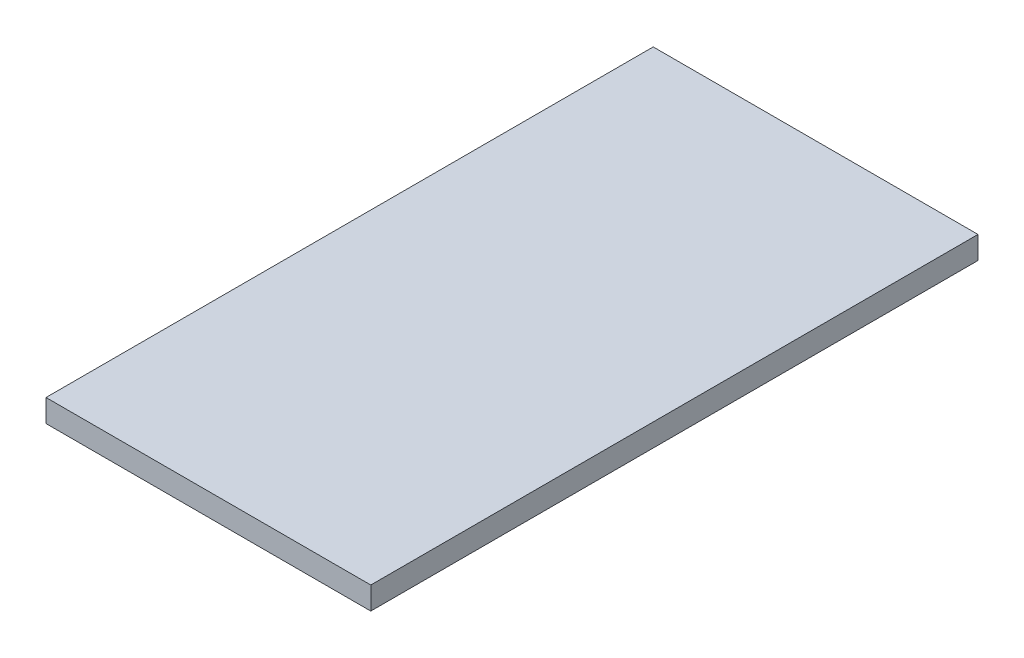
SolidWorks part; units mm, degrees
ref_plane "前视基准面" through (0, 0, 0) normal (0, 0, 1) x (1, 0, 0)
ref_plane "上视基准面" through (0, 0, 0) normal (0, 1, 0) x (1, 0, 0)
ref_plane "右视基准面" through (0, 0, 0) normal (1, 0, 0) x (0, 0, -1)
sketch "草图1" plane through (0, 0, 0) normal (0, 1, 0) x (1, 0, 0)
  line L0 (0, 30.0941) -> (0, -34.2305) construction
  line L1 (-11.5, 21.5) -> (11.5, 21.5)
  line L2 (-11.5, 21.5) -> (-11.5, -21.5)
  line L3 (-11.5, -21.5) -> (11.5, -21.5)
  line L4 (11.5, 21.5) -> (11.5, -21.5)
  line L5 (-19.7366, 0) -> (21.947, 0) construction
  dimension "D1" = 43
  dimension "D2" = 23
extrude "凸台-拉伸1" add sketch "草图1" along normal blind 1.6
